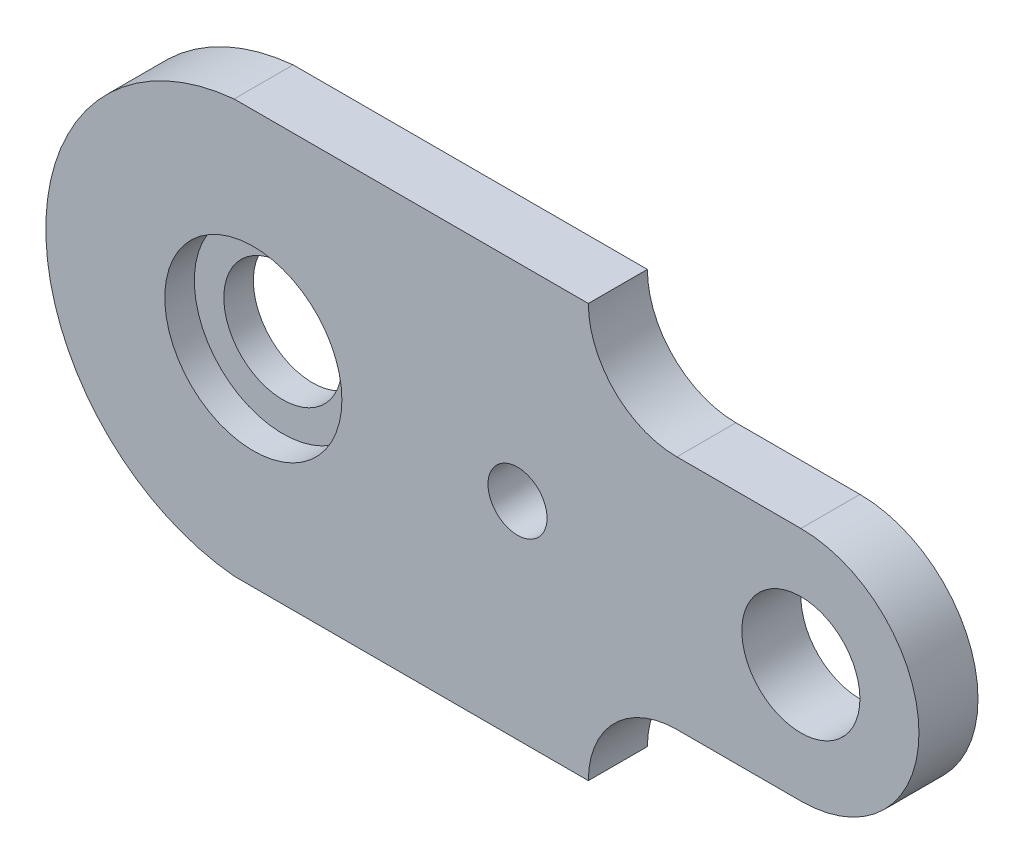
SolidWorks part; units mm, degrees
ref_plane "Front Plane" through (0, 0, 0) normal (0, 0, 1) x (1, 0, 0)
ref_plane "Top Plane" through (0, 0, 0) normal (0, 1, 0) x (1, 0, 0)
ref_plane "Right Plane" through (0, 0, 0) normal (1, 0, 0) x (0, 0, -1)
sketch "Sketch2" plane through (0, 0, 0) normal (0, 0, 1) x (1, 0, 0)
  line L9 (-207.0504, 98.4723) -> (-147.0504, 98.4723)
  line L10 (-207.0504, 28.4723) -> (-147.0504, 28.4723)
  line L11 (-111.0504, 43.4723) -> (-132.0504, 43.4723)
  line L12 (-132.0504, 83.4723) -> (-111.0504, 83.4723)
  arc A5 (-207.0504, 28.4723) -> (-207.0504, 98.4723) centre (-203.7932, 63.4723) cw
  arc A8 (-147.0504, 28.4723) -> (-132.0504, 43.4723) centre (-132.0504, 28.4723) cw
  arc A9 (-147.0504, 98.4723) -> (-132.0504, 83.4723) centre (-132.0504, 98.4723) ccw
  circle A10 centre (-111.0504, 63.4723) radius 10
  arc A11 (-111.0504, 83.4723) -> (-111.0504, 43.4723) centre (-111.0504, 63.4723) cw
  circle A13 centre (-159.0504, 63.4723) radius 5
  dimension "D1" = 10
  dimension "D4" = 15
  dimension "D5" = 36
  dimension "D9" = 20
extrude "Boss-Extrude3" add sketch "Sketch2" along normal blind 10
sketch "Sketch3" plane through (0, 0, 10) normal (0, 0, 1) x (1, 0, 0)
  circle A1 centre (-203.7932, 63.4723) radius 15
  dimension "D2" = 30
extrude "Cut-Extrude1" cut sketch "Sketch3" against normal blind 5
sketch "Sketch4" plane through (0, 0, 5) normal (0, 0, 1) x (1, 0, 0)
  circle A0 centre (-203.7932, 63.4723) radius 10
  dimension "D1" = 20
extrude "Cut-Extrude2" cut sketch "Sketch4" against normal through all
